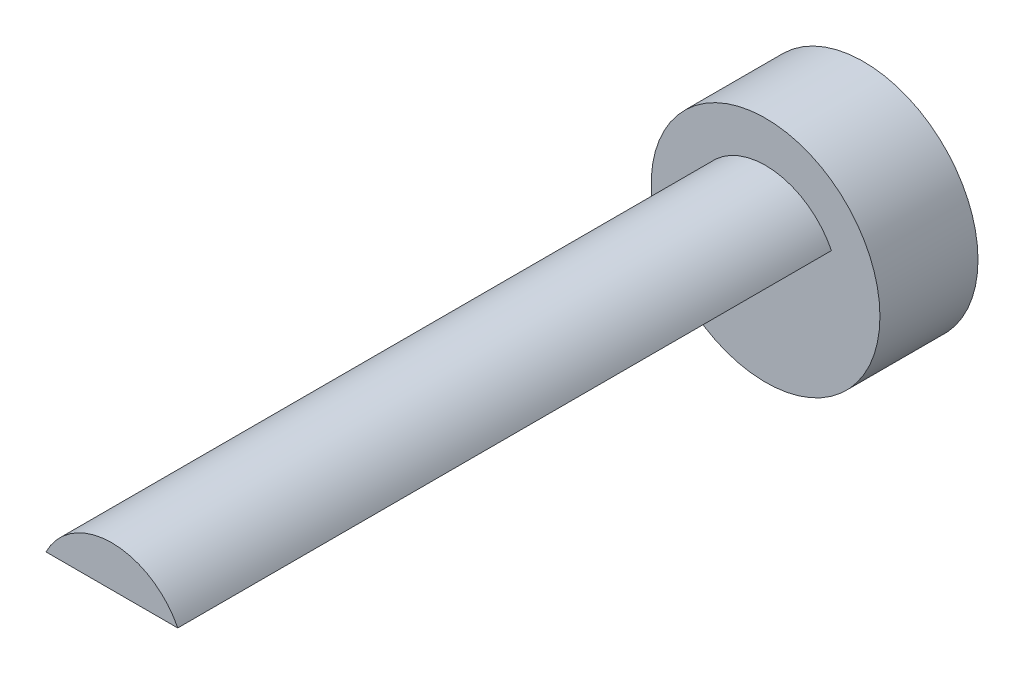
SolidWorks part; units mm, degrees
ref_plane "Front Plane" through (0, 0, 0) normal (0, 0, 1) x (1, 0, 0)
ref_plane "Top Plane" through (0, 0, 0) normal (0, 1, 0) x (1, 0, 0)
ref_plane "Right Plane" through (0, 0, 0) normal (1, 0, 0) x (0, 0, -1)
sketch "Sketch1" plane through (0, 0, 0) normal (0, 0, 1) x (1, 0, 0)
  line L0 (-3.4737, 1) -> (4.1684, 1)
  circle A0 centre (0, 0) radius 3.5
  dimension "D2" = 7
  dimension "D1" = 1
extrude "Boss-Extrude1" add sketch "Sketch1" along normal blind 3 contours L0 A0
sketch "Sketch2" plane through (0, 0, 3) normal (0, 0, 1) x (1, 0, 0)
  line L0 (-2.0156, 1) -> (2.0156, 1)
  circle A0 centre (0, 0) radius 2.25
  dimension "D1" = 4.5
  dimension "D2" = 1
extrude "Boss-Extrude2" add sketch "Sketch2" along normal blind 20
